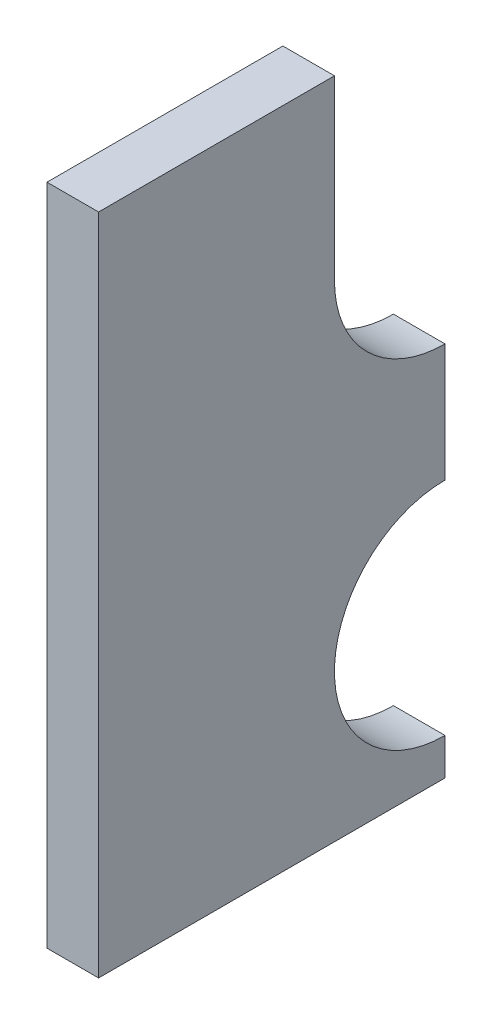
SolidWorks part; units mm, degrees
ref_plane "Front Plane" through (0, 0, 0) normal (0, 0, 1) x (1, 0, 0)
ref_plane "Top Plane" through (0, 0, 0) normal (0, 1, 0) x (1, 0, 0)
ref_plane "Right Plane" through (0, 0, 0) normal (1, 0, 0) x (0, 0, -1)
sketch "Sketch1" plane through (0, 0, 0) normal (0, 0, 1) x (1, 0, 0)
  line L1 (0, 0) -> (17.78, 0)
  line L2 (0, 0) -> (0, -228.6)
  line L3 (0, -228.6) -> (17.78, -228.6)
  line L4 (17.78, 0) -> (17.78, -228.6)
  dimension "D1" = 228.6
  dimension "D2" = 17.78
extrude "Boss-Extrude1" add sketch "Sketch1" along normal blind 119.38
sketch "Sketch2" plane through (17.78, 0, 0) normal (1, 0, 0) x (0, 0, -1)
  line L0 (0, -228.6) -> (0, 0) construction
  line L1 (-119.38, -228.6) -> (0, -228.6) construction
  line L2 (-38.1, -60.96) -> (-38.1, 0)
  line L3 (-119.38, 0) -> (0, 0) construction
  line L4 (-38.1, 0) -> (0, 0)
  line L5 (0, 0) -> (0, -22.86)
  line L6 (0, -215.9) -> (0, -139.7)
  line L7 (0, -99.06) -> (0, -22.86)
  arc A0 (0, -139.7) -> (0, -215.9) centre (0, -177.8) ccw
  arc A1 (-38.1, -60.96) -> (0, -99.06) centre (0, -60.96) ccw
  dimension "D1" = 60.96
  dimension "D3" = 76.2
  dimension "D4" = 76.2
  dimension "D2" = 50.8
extrude "Cut-Extrude1" cut sketch "Sketch2" against normal through all
